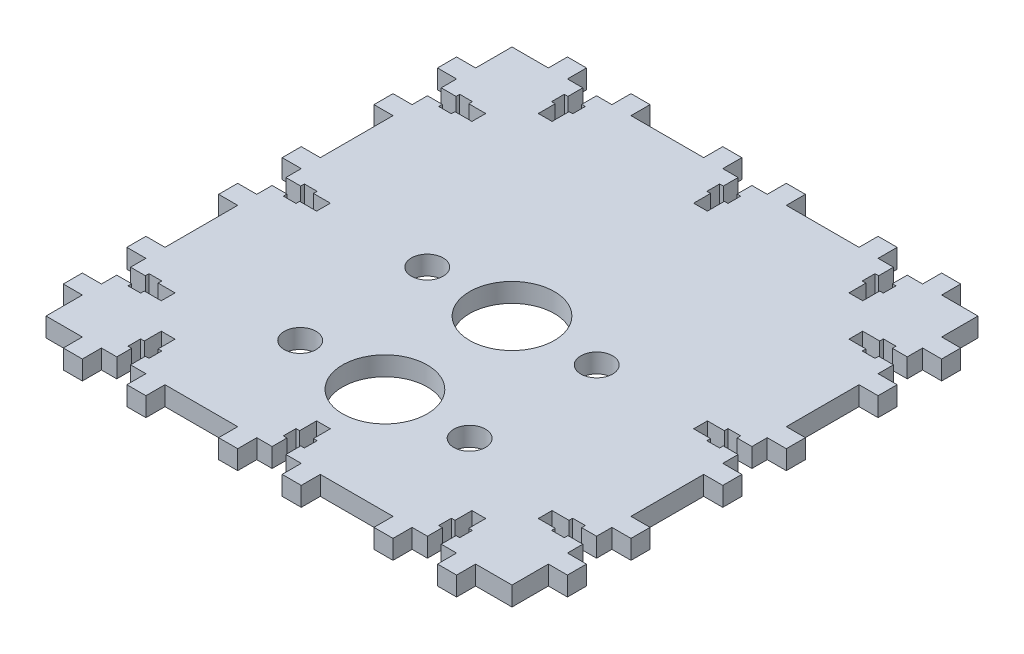
SolidWorks part; units mm, degrees
ref_plane "Front Plane" through (0, 0, 0) normal (0, 0, 1) x (1, 0, 0)
ref_plane "Top Plane" through (0, 0, 0) normal (0, 1, 0) x (1, 0, 0)
ref_plane "Right Plane" through (0, 0, 0) normal (1, 0, 0) x (0, 0, -1)
sketch "Sketch1" plane through (0, 0, 0) normal (0, 1, 0) x (1, 0, 0)
  line L0 (0, 0) -> (0, -110) construction
  line L1 (-110, -110) -> (110, -110)
  line L2 (-110, -110) -> (-110, 110)
  line L3 (-110, 110) -> (110, 110)
  line L4 (110, -110) -> (110, 110)
  line L5 (-110, -110) -> (110, 110) construction
  line L6 (-110, 110) -> (110, -110) construction
  line L7 (0, 0) -> (110, 0) construction
  line L8 (110, -30) -> (-110, -30) construction
  line L9 (-110, 72.5) -> (110, 72.5) construction
  line L10 (0, 0) -> (0, 98.7792) construction
  circle A0 centre (0, 0) radius 20
  circle A1 centre (40, 0) radius 7.5
  circle A2 centre (-40, 0) radius 7.5
  circle A3 centre (-40, -60) radius 7.5
  circle A4 centre (0, -60) radius 20
  circle A5 centre (40, -60) radius 7.5
  point P0 (0, 0)
  point P28 (0, 0)
  line B0 (-92.8333, -110) -> (-92.8333, -119)
  line B1 (-92.8333, -119) -> (-83.8333, -119)
  line B2 (-83.8333, -119) -> (-83.8333, -110)
  line B3 (-83.8333, -110) -> (-76.5833, -110)
  line B4 (-76.5833, -110) -> (-76.5833, -103)
  line B5 (-76.5833, -103) -> (-78.3083, -103)
  line B6 (-78.3083, -103) -> (-78.3083, -97)
  line B7 (-78.3083, -97) -> (-76.5833, -97)
  line B8 (-76.5833, -97) -> (-76.5833, -89)
  line B9 (-76.5833, -89) -> (-70.0833, -89)
  line B10 (-73.3333, -89) -> (-73.3333, -110) construction
  line B11 (-70.0833, -97) -> (-70.0833, -89)
  line B12 (-68.3583, -97) -> (-70.0833, -97)
  line B13 (-68.3583, -103) -> (-68.3583, -97)
  line B14 (-70.0833, -103) -> (-68.3583, -103)
  line B15 (-70.0833, -110) -> (-70.0833, -103)
  line B16 (-62.8333, -110) -> (-70.0833, -110)
  line B17 (-62.8333, -119) -> (-62.8333, -110)
  line B18 (-53.8333, -119) -> (-62.8333, -119)
  line B19 (-53.8333, -110) -> (-53.8333, -119)
  line B20 (-19.5, -110) -> (-19.5, -119)
  line B21 (-19.5, -119) -> (-10.5, -119)
  line B22 (-10.5, -119) -> (-10.5, -110)
  line B23 (-10.5, -110) -> (-3.25, -110)
  line B24 (-3.25, -110) -> (-3.25, -103)
  line B25 (-3.25, -103) -> (-4.975, -103)
  line B26 (-4.975, -103) -> (-4.975, -97)
  line B27 (-4.975, -97) -> (-3.25, -97)
  line B28 (-3.25, -97) -> (-3.25, -89)
  line B29 (-3.25, -89) -> (3.25, -89)
  line B30 (0, -89) -> (0, -110) construction
  line B31 (3.25, -97) -> (3.25, -89)
  line B32 (4.975, -97) -> (3.25, -97)
  line B33 (4.975, -103) -> (4.975, -97)
  line B34 (3.25, -103) -> (4.975, -103)
  line B35 (3.25, -110) -> (3.25, -103)
  line B36 (10.5, -110) -> (3.25, -110)
  line B37 (10.5, -119) -> (10.5, -110)
  line B38 (19.5, -119) -> (10.5, -119)
  line B39 (19.5, -110) -> (19.5, -119)
  line B40 (53.8333, -110) -> (53.8333, -119)
  line B41 (53.8333, -119) -> (62.8333, -119)
  line B42 (62.8333, -119) -> (62.8333, -110)
  line B43 (62.8333, -110) -> (70.0833, -110)
  line B44 (70.0833, -110) -> (70.0833, -103)
  line B45 (70.0833, -103) -> (68.3583, -103)
  line B46 (68.3583, -103) -> (68.3583, -97)
  line B47 (68.3583, -97) -> (70.0833, -97)
  line B48 (70.0833, -97) -> (70.0833, -89)
  line B49 (70.0833, -89) -> (76.5833, -89)
  line B50 (73.3333, -89) -> (73.3333, -110) construction
  line B51 (76.5833, -97) -> (76.5833, -89)
  line B52 (78.3083, -97) -> (76.5833, -97)
  line B53 (78.3083, -103) -> (78.3083, -97)
  line B54 (76.5833, -103) -> (78.3083, -103)
  line B55 (76.5833, -110) -> (76.5833, -103)
  line B56 (83.8333, -110) -> (76.5833, -110)
  line B57 (83.8333, -119) -> (83.8333, -110)
  line B58 (92.8333, -119) -> (83.8333, -119)
  line B59 (92.8333, -110) -> (92.8333, -119)
  line B60 (-110, 92.8333) -> (-119, 92.8333)
  line B61 (-119, 92.8333) -> (-119, 83.8333)
  line B62 (-119, 83.8333) -> (-110, 83.8333)
  line B63 (-110, 83.8333) -> (-110, 76.5833)
  line B64 (-110, 76.5833) -> (-103, 76.5833)
  line B65 (-103, 76.5833) -> (-103, 78.3083)
  line B66 (-103, 78.3083) -> (-97, 78.3083)
  line B67 (-97, 78.3083) -> (-97, 76.5833)
  line B68 (-97, 76.5833) -> (-89, 76.5833)
  line B69 (-89, 76.5833) -> (-89, 70.0833)
  line B70 (-89, 73.3333) -> (-110, 73.3333) construction
  line B71 (-97, 70.0833) -> (-89, 70.0833)
  line B72 (-97, 68.3583) -> (-97, 70.0833)
  line B73 (-103, 68.3583) -> (-97, 68.3583)
  line B74 (-103, 70.0833) -> (-103, 68.3583)
  line B75 (-110, 70.0833) -> (-103, 70.0833)
  line B76 (-110, 62.8333) -> (-110, 70.0833)
  line B77 (-119, 62.8333) -> (-110, 62.8333)
  line B78 (-119, 53.8333) -> (-119, 62.8333)
  line B79 (-110, 53.8333) -> (-119, 53.8333)
  line B80 (-110, 19.5) -> (-119, 19.5)
  line B81 (-119, 19.5) -> (-119, 10.5)
  line B82 (-119, 10.5) -> (-110, 10.5)
  line B83 (-110, 10.5) -> (-110, 3.25)
  line B84 (-110, 3.25) -> (-103, 3.25)
  line B85 (-103, 3.25) -> (-103, 4.975)
  line B86 (-103, 4.975) -> (-97, 4.975)
  line B87 (-97, 4.975) -> (-97, 3.25)
  line B88 (-97, 3.25) -> (-89, 3.25)
  line B89 (-89, 3.25) -> (-89, -3.25)
  line B90 (-89, 0) -> (-110, 0) construction
  line B91 (-97, -3.25) -> (-89, -3.25)
  line B92 (-97, -4.975) -> (-97, -3.25)
  line B93 (-103, -4.975) -> (-97, -4.975)
  line B94 (-103, -3.25) -> (-103, -4.975)
  line B95 (-110, -3.25) -> (-103, -3.25)
  line B96 (-110, -10.5) -> (-110, -3.25)
  line B97 (-119, -10.5) -> (-110, -10.5)
  line B98 (-119, -19.5) -> (-119, -10.5)
  line B99 (-110, -19.5) -> (-119, -19.5)
  line B100 (-110, -53.8333) -> (-119, -53.8333)
  line B101 (-119, -53.8333) -> (-119, -62.8333)
  line B102 (-119, -62.8333) -> (-110, -62.8333)
  line B103 (-110, -62.8333) -> (-110, -70.0833)
  line B104 (-110, -70.0833) -> (-103, -70.0833)
  line B105 (-103, -70.0833) -> (-103, -68.3583)
  line B106 (-103, -68.3583) -> (-97, -68.3583)
  line B107 (-97, -68.3583) -> (-97, -70.0833)
  line B108 (-97, -70.0833) -> (-89, -70.0833)
  line B109 (-89, -70.0833) -> (-89, -76.5833)
  line B110 (-89, -73.3333) -> (-110, -73.3333) construction
  line B111 (-97, -76.5833) -> (-89, -76.5833)
  line B112 (-97, -78.3083) -> (-97, -76.5833)
  line B113 (-103, -78.3083) -> (-97, -78.3083)
  line B114 (-103, -76.5833) -> (-103, -78.3083)
  line B115 (-110, -76.5833) -> (-103, -76.5833)
  line B116 (-110, -83.8333) -> (-110, -76.5833)
  line B117 (-119, -83.8333) -> (-110, -83.8333)
  line B118 (-119, -92.8333) -> (-119, -83.8333)
  line B119 (-110, -92.8333) -> (-119, -92.8333)
  line B120 (92.8333, 110) -> (92.8333, 119)
  line B121 (92.8333, 119) -> (83.8333, 119)
  line B122 (83.8333, 119) -> (83.8333, 110)
  line B123 (83.8333, 110) -> (76.5833, 110)
  line B124 (76.5833, 110) -> (76.5833, 103)
  line B125 (76.5833, 103) -> (78.3083, 103)
  line B126 (78.3083, 103) -> (78.3083, 97)
  line B127 (78.3083, 97) -> (76.5833, 97)
  line B128 (76.5833, 97) -> (76.5833, 89)
  line B129 (76.5833, 89) -> (70.0833, 89)
  line B130 (73.3333, 89) -> (73.3333, 110) construction
  line B131 (70.0833, 97) -> (70.0833, 89)
  line B132 (68.3583, 97) -> (70.0833, 97)
  line B133 (68.3583, 103) -> (68.3583, 97)
  line B134 (70.0833, 103) -> (68.3583, 103)
  line B135 (70.0833, 110) -> (70.0833, 103)
  line B136 (62.8333, 110) -> (70.0833, 110)
  line B137 (62.8333, 119) -> (62.8333, 110)
  line B138 (53.8333, 119) -> (62.8333, 119)
  line B139 (53.8333, 110) -> (53.8333, 119)
  line B140 (19.5, 110) -> (19.5, 119)
  line B141 (19.5, 119) -> (10.5, 119)
  line B142 (10.5, 119) -> (10.5, 110)
  line B143 (10.5, 110) -> (3.25, 110)
  line B144 (3.25, 110) -> (3.25, 103)
  line B145 (3.25, 103) -> (4.975, 103)
  line B146 (4.975, 103) -> (4.975, 97)
  line B147 (4.975, 97) -> (3.25, 97)
  line B148 (3.25, 97) -> (3.25, 89)
  line B149 (3.25, 89) -> (-3.25, 89)
  line B150 (0, 89) -> (0, 110) construction
  line B151 (-3.25, 97) -> (-3.25, 89)
  line B152 (-4.975, 97) -> (-3.25, 97)
  line B153 (-4.975, 103) -> (-4.975, 97)
  line B154 (-3.25, 103) -> (-4.975, 103)
  line B155 (-3.25, 110) -> (-3.25, 103)
  line B156 (-10.5, 110) -> (-3.25, 110)
  line B157 (-10.5, 119) -> (-10.5, 110)
  line B158 (-19.5, 119) -> (-10.5, 119)
  line B159 (-19.5, 110) -> (-19.5, 119)
  line B160 (-53.8333, 110) -> (-53.8333, 119)
  line B161 (-53.8333, 119) -> (-62.8333, 119)
  line B162 (-62.8333, 119) -> (-62.8333, 110)
  line B163 (-62.8333, 110) -> (-70.0833, 110)
  line B164 (-70.0833, 110) -> (-70.0833, 103)
  line B165 (-70.0833, 103) -> (-68.3583, 103)
  line B166 (-68.3583, 103) -> (-68.3583, 97)
  line B167 (-68.3583, 97) -> (-70.0833, 97)
  line B168 (-70.0833, 97) -> (-70.0833, 89)
  line B169 (-70.0833, 89) -> (-76.5833, 89)
  line B170 (-73.3333, 89) -> (-73.3333, 110) construction
  line B171 (-76.5833, 97) -> (-76.5833, 89)
  line B172 (-78.3083, 97) -> (-76.5833, 97)
  line B173 (-78.3083, 103) -> (-78.3083, 97)
  line B174 (-76.5833, 103) -> (-78.3083, 103)
  line B175 (-76.5833, 110) -> (-76.5833, 103)
  line B176 (-83.8333, 110) -> (-76.5833, 110)
  line B177 (-83.8333, 119) -> (-83.8333, 110)
  line B178 (-92.8333, 119) -> (-83.8333, 119)
  line B179 (-92.8333, 110) -> (-92.8333, 119)
  line B180 (110, -92.8333) -> (119, -92.8333)
  line B181 (119, -92.8333) -> (119, -83.8333)
  line B182 (119, -83.8333) -> (110, -83.8333)
  line B183 (110, -83.8333) -> (110, -76.5833)
  line B184 (110, -76.5833) -> (103, -76.5833)
  line B185 (103, -76.5833) -> (103, -78.3083)
  line B186 (103, -78.3083) -> (97, -78.3083)
  line B187 (97, -78.3083) -> (97, -76.5833)
  line B188 (97, -76.5833) -> (89, -76.5833)
  line B189 (89, -76.5833) -> (89, -70.0833)
  line B190 (89, -73.3333) -> (110, -73.3333) construction
  line B191 (97, -70.0833) -> (89, -70.0833)
  line B192 (97, -68.3583) -> (97, -70.0833)
  line B193 (103, -68.3583) -> (97, -68.3583)
  line B194 (103, -70.0833) -> (103, -68.3583)
  line B195 (110, -70.0833) -> (103, -70.0833)
  line B196 (110, -62.8333) -> (110, -70.0833)
  line B197 (119, -62.8333) -> (110, -62.8333)
  line B198 (119, -53.8333) -> (119, -62.8333)
  line B199 (110, -53.8333) -> (119, -53.8333)
  line B200 (110, -19.5) -> (119, -19.5)
  line B201 (119, -19.5) -> (119, -10.5)
  line B202 (119, -10.5) -> (110, -10.5)
  line B203 (110, -10.5) -> (110, -3.25)
  line B204 (110, -3.25) -> (103, -3.25)
  line B205 (103, -3.25) -> (103, -4.975)
  line B206 (103, -4.975) -> (97, -4.975)
  line B207 (97, -4.975) -> (97, -3.25)
  line B208 (97, -3.25) -> (89, -3.25)
  line B209 (89, -3.25) -> (89, 3.25)
  line B210 (89, 0) -> (110, 0) construction
  line B211 (97, 3.25) -> (89, 3.25)
  line B212 (97, 4.975) -> (97, 3.25)
  line B213 (103, 4.975) -> (97, 4.975)
  line B214 (103, 3.25) -> (103, 4.975)
  line B215 (110, 3.25) -> (103, 3.25)
  line B216 (110, 10.5) -> (110, 3.25)
  line B217 (119, 10.5) -> (110, 10.5)
  line B218 (119, 19.5) -> (119, 10.5)
  line B219 (110, 19.5) -> (119, 19.5)
  line B220 (110, 53.8333) -> (119, 53.8333)
  line B221 (119, 53.8333) -> (119, 62.8333)
  line B222 (119, 62.8333) -> (110, 62.8333)
  line B223 (110, 62.8333) -> (110, 70.0833)
  line B224 (110, 70.0833) -> (103, 70.0833)
  line B225 (103, 70.0833) -> (103, 68.3583)
  line B226 (103, 68.3583) -> (97, 68.3583)
  line B227 (97, 68.3583) -> (97, 70.0833)
  line B228 (97, 70.0833) -> (89, 70.0833)
  line B229 (89, 70.0833) -> (89, 76.5833)
  line B230 (89, 73.3333) -> (110, 73.3333) construction
  line B231 (97, 76.5833) -> (89, 76.5833)
  line B232 (97, 78.3083) -> (97, 76.5833)
  line B233 (103, 78.3083) -> (97, 78.3083)
  line B234 (103, 76.5833) -> (103, 78.3083)
  line B235 (110, 76.5833) -> (103, 76.5833)
  line B236 (110, 83.8333) -> (110, 76.5833)
  line B237 (119, 83.8333) -> (110, 83.8333)
  line B238 (119, 92.8333) -> (119, 83.8333)
  line B239 (110, 92.8333) -> (119, 92.8333)
  dimension "D7" = 40
  dimension "D8" = 15
  dimension "D1" = 220
  dimension "D2" = 220
  dimension "D3" = 36.6667
  dimension "D4" = 4
  dimension "D9" = 40
  dimension "D10" = 30
sketch_block_instance "Plot_9mm_M6_bois-1"
sketch_block "Plot_9mm_M6_bois" parameters "D1"=9, "D2"=9, "D3"=16, "D4"=30, "D5"=9.95, "D6"=6.5, "D7"=6, "D8"=8
sketch_block_instance "Plot_9mm_M6_bois-2"
sketch_block_instance "Plot_9mm_M6_bois-3"
sketch_block_instance "Plot_9mm_M6_bois-5"
sketch_block_instance "Plot_9mm_M6_bois-6"
sketch_block_instance "Plot_9mm_M6_bois-7"
sketch_block_instance "Plot_9mm_M6_bois-8"
sketch_block_instance "Plot_9mm_M6_bois-9"
sketch_block_instance "Plot_9mm_M6_bois-10"
sketch_block_instance "Plot_9mm_M6_bois-11"
sketch_block_instance "Plot_9mm_M6_bois-12"
sketch_block_instance "Plot_9mm_M6_bois-13"
extrude "Boss-Extrude1" add sketch "Sketch1" along normal blind 9
sketch "Sketch3" plane through (0, 9, 0) normal (0, 1, 0) x (1, 0, 0)
  line L0 (-110, 44.2946) -> (110, 44.2946) construction
  text T0 "<b>Кирилл</b> <i>2000</i>" font "Century Gothic" height 20
